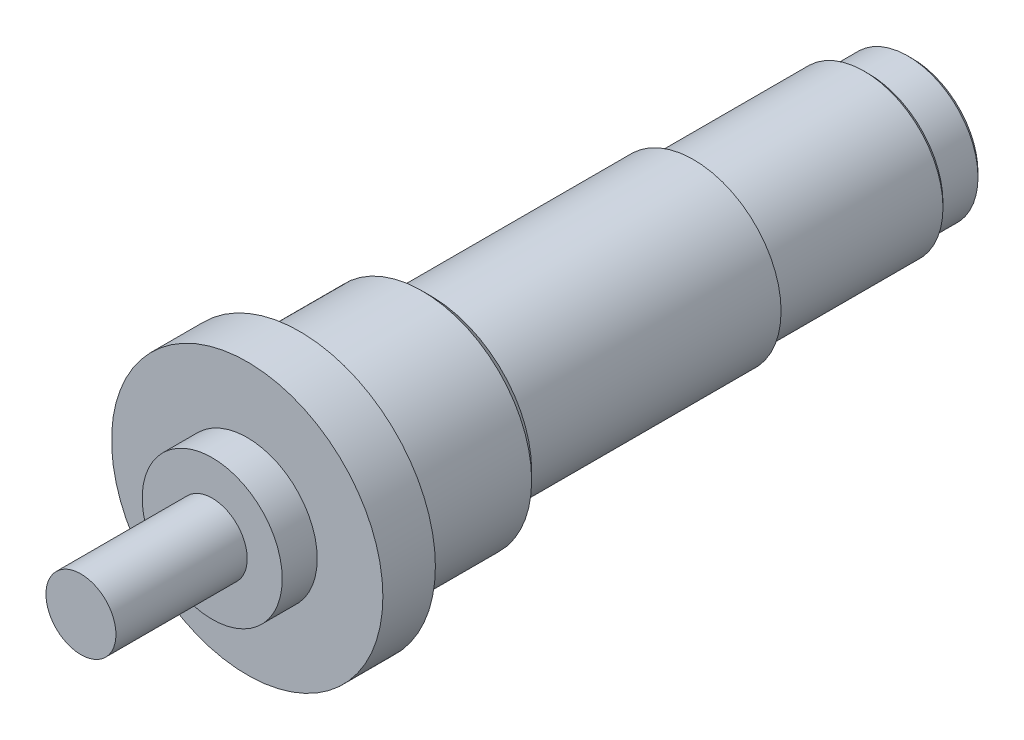
SolidWorks part; units mm, degrees
ref_plane "前视基准面" through (0, 0, 0) normal (0, 0, 1) x (1, 0, 0)
ref_plane "上视基准面" through (0, 0, 0) normal (0, 1, 0) x (1, 0, 0)
ref_plane "右视基准面" through (0, 0, 0) normal (1, 0, 0) x (0, 0, -1)
other "Configuration Table"
sketch "草图1" plane through (0, 0, 0) normal (1, 0, 0) x (0, 0, -1)
  line L0 (-113.7143, 0) -> (140, 0) construction
  line L1 (-47.5, 0) -> (-47.5, 4)
  line L2 (-47.5, 4) -> (-32.5, 4)
  line L3 (-32.5, 4) -> (-32.5, 8)
  line L4 (-32.5, 8) -> (-28.5, 8)
  line L5 (-28.5, 8) -> (-28.5, 15.5)
  line L6 (-28.5, 15.5) -> (-22.5, 15.5)
  line L7 (-22.5, 15.5) -> (-22.5, 12.5)
  line L8 (-22.5, 12.5) -> (-7.5, 12.5)
  line L9 (-7.5, 12.5) -> (-7.5, 10)
  line L11 (47.5, 8) -> (47.5, 0)
  line L12 (47.5, 0) -> (-47.5, 0)
  line L17 (42.5, 8) -> (47.5, 8)
  line L18 (22.5, 9) -> (42.5, 9)
  line L19 (42.5, 9) -> (42.5, 8)
  line L20 (-7.5, 10) -> (22.5, 10)
  line L21 (22.5, 10) -> (22.5, 9)
  point P6 (0, 0)
  dimension "D2" = 18
  dimension "D3" = 15
  dimension "D4" = 8
  dimension "D5" = 15
  dimension "D6" = 16
  dimension "D7" = 16
  dimension "D8" = 6
  dimension "D9" = 25
  dimension "D10" = 31
  dimension "D11" = 4
  dimension "D14" = 20
  dimension "D15" = 5
  dimension "D16" = 20
  dimension "D17" = 30
revolve "旋转1" add sketch "草图1" angle 360 about L0
chamfer "倒角1" distance 1 angle 45 1 edges at (12.5, 0, 7.5)
chamfer "倒角2" distance 0.5 angle 45 2 edges at (8, 0, -47.5) (9, 0, -42.5)
